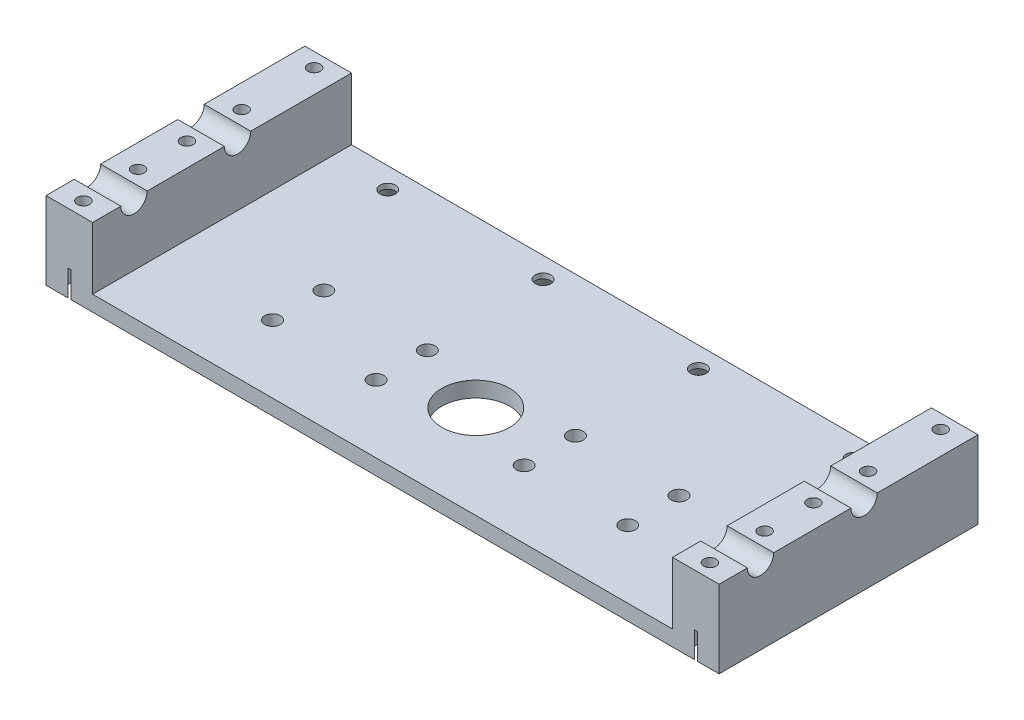
SolidWorks part; units mm, degrees
ref_plane "前视基准面" through (0, 0, 0) normal (0, 0, 1) x (1, 0, 0)
ref_plane "上视基准面" through (0, 0, 0) normal (0, 1, 0) x (1, 0, 0)
ref_plane "右视基准面" through (0, 0, 0) normal (1, 0, 0) x (0, 0, -1)
sketch "草图2" plane through (0, 0, 0) normal (1, 0, 0) x (0, 0, -1)
  line L0 (-7.45, 12) -> (7.45, 12)
  line L1 (-18, 0) -> (32, 0)
  line L2 (-18, 0) -> (-18, 12)
  line L3 (-18, 12) -> (-12.55, 12)
  line L4 (32, 0) -> (32, 12)
  line L5 (12.55, 12) -> (32, 12)
  arc A0 (7.45, 12) -> (12.55, 12) centre (10, 12) ccw
  arc A1 (-12.55, 12) -> (-7.45, 12) centre (-10, 12) ccw
  dimension "D4" = 5.1
  dimension "D5" = 5.1
  dimension "D1" = 12
  dimension "D2" = 50
  dimension "D3" = 18
  dimension "D6" = 20
  dimension "D7" = 10
extrude "凸台-拉伸1" add sketch "草图2" along normal mid plane 130
sketch "草图4" plane through (0, 0, 0) normal (0, -1, 0) x (1, 0, 0)
  line L0 (65, -32) -> (-65, -32) construction
  line L1 (-56, -32) -> (56, -32)
  line L2 (-56, -32) -> (-56, 18)
  line L3 (-56, 18) -> (56, 18)
  line L4 (56, -32) -> (56, 18)
  line L5 (65, 18) -> (-65, 18) construction
  dimension "D1" = 112
  dimension "D2" = 56
extrude "切除-拉伸1" cut sketch "草图4" against normal blind 20
sketch "草图5" plane through (0, 0, 0) normal (0, -1, 0) x (1, 0, 0)
  line L0 (-37.5732, 0) -> (40.267, 0) construction
  line L1 (-65, 18) -> (65, 18)
  line L2 (-65, 18) -> (-65, -32)
  line L3 (-65, -32) -> (65, -32)
  line L4 (65, 18) -> (65, -32)
  line L5 (0, 0) -> (0, -10.8475) construction
  circle A0 centre (0, 0) radius 6.55
  circle A1 centre (-14.3, 4.95) radius 1.5
  circle A2 centre (34.3, -4.95) radius 1.5
  circle A3 centre (34.3, 4.95) radius 1.5
  circle A4 centre (-14.3, -4.95) radius 1.5
  circle A5 centre (-34.3, 4.95) radius 1.5
  circle A6 centre (-34.3, -4.95) radius 1.5
  circle A7 centre (14.3, -4.95) radius 1.5
  circle A8 centre (14.3, 4.95) radius 1.5
  dimension "D2" = 13.1
  dimension "D3" = 3
  dimension "D7" = 3
  dimension "D1" = 50
  dimension "D4" = 4.95
  dimension "D5" = 34.3
  dimension "D6" = 48.6
extrude "凸台-拉伸2" add sketch "草图5" along normal blind 3
sketch "草图6" plane through (0, 12, 0) normal (0, 1, 0) x (1, 0, 0)
  line L0 (-60.5, 32) -> (-60.5, -18) construction
  line L1 (-56, 32) -> (-65, 32) construction
  line L2 (-56, -18) -> (-65, -18) construction
  line L3 (-65, -15.275) -> (-56, -15.275) construction
  line L4 (-65, -12.55) -> (-65, -18) construction
  line L5 (-56, -18) -> (-56, -12.55) construction
  line L6 (-65, -10) -> (-57.051, -10) construction
  line L7 (-65, -7.45) -> (-65, -12.55) construction
  line L8 (-65, 0) -> (-57.051, 0) construction
  line L9 (-65, 7.45) -> (-65, -7.45) construction
  line L10 (-65, 22.275) -> (-50.7357, 22.275) construction
  line L11 (-65, 32) -> (-65, 12.55) construction
  line L12 (0, 0) -> (0, 35.7346) construction
  circle A0 centre (-60.5, -15.275) radius 1.2
  circle A1 centre (-60.5, -4.725) radius 1.2
  circle A2 centre (-60.5, 15.275) radius 1.2
  circle A3 centre (-60.5, 4.725) radius 1.2
  circle A4 centre (-60.5, 29.275) radius 1.2
  circle A5 centre (60.5, 29.275) radius 1.2
  circle A6 centre (60.5, 4.725) radius 1.2
  circle A7 centre (60.5, 15.275) radius 1.2
  circle A8 centre (60.5, -4.725) radius 1.2
  circle A9 centre (60.5, -15.275) radius 1.2
  dimension "D1" = 2.4
extrude "切除-拉伸2" cut sketch "草图6" against normal blind 20
sketch "草图7" plane through (0, -3, 0) normal (0, -1, 0) x (1, 0, 0)
  line L0 (-65, -28) -> (69.8008, -28) construction
  line L1 (-65, 18) -> (-65, -32) construction
  line L2 (0, 0) -> (0, -29.8452) construction
  circle A0 centre (-15, -28) radius 1.5
  circle A1 centre (-45, -28) radius 1.5
  circle A2 centre (45, -28) radius 1.5
  circle A3 centre (15, -28) radius 1.5
  dimension "D2" = 3
  dimension "D4" = 3
  dimension "D1" = 4
  dimension "D3" = 15
  dimension "D5" = 30
extrude "切除-拉伸3" cut sketch "草图7" against normal blind 20
sketch "草图8" plane through (0, -3, 0) normal (0, -1, 0) x (1, 0, 0)
  line L0 (0, 0) -> (0, -34.2029) construction
  circle A0 centre (-45, -28) radius 2.65
  circle A1 centre (-15, -28) radius 2.65
  circle A2 centre (15, -28) radius 2.65
  circle A3 centre (45, -28) radius 2.65
  dimension "D1" = 5.3
  dimension "D2" = 5.3
extrude "切除-拉伸4" cut sketch "草图8" against normal blind 2 draft 25
sketch "草图9" plane through (0, -3, 0) normal (0, -1, 0) x (1, 0, 0)
  line L1 (-58, -3.2816) -> (-60.5, -1.8382)
  line L2 (-60.5, -1.8382) -> (-63, -3.2816)
  line L3 (-63, -3.2816) -> (-63, -6.1684)
  line L4 (-63, -6.1684) -> (-60.5, -7.6118)
  line L5 (-60.5, -7.6118) -> (-58, -6.1684)
  line L6 (-58, -6.1684) -> (-58, -3.2816)
  line L7 (-58, -13.8316) -> (-60.5, -12.3882)
  line L8 (-60.5, -12.3882) -> (-63, -13.8316)
  line L9 (-63, -13.8316) -> (-63, -16.7184)
  line L10 (-63, -16.7184) -> (-60.5, -18.1618)
  line L11 (-60.5, -18.1618) -> (-58, -16.7184)
  line L12 (-58, -16.7184) -> (-58, -13.8316)
  line L13 (-58, -27.8316) -> (-60.5, -26.3882)
  line L14 (-60.5, -26.3882) -> (-63, -27.8316)
  line L15 (-63, -27.8316) -> (-63, -30.7184)
  line L16 (-63, -30.7184) -> (-60.5, -32.1618)
  line L17 (-60.5, -32.1618) -> (-58, -30.7184)
  line L18 (-58, -30.7184) -> (-58, -27.8316)
  line L19 (-58, 6.1684) -> (-60.5, 7.6118)
  line L20 (-60.5, 7.6118) -> (-63, 6.1684)
  line L21 (-63, 6.1684) -> (-63, 3.2816)
  line L22 (-63, 3.2816) -> (-60.5, 1.8382)
  line L23 (-60.5, 1.8382) -> (-58, 3.2816)
  line L24 (-58, 3.2816) -> (-58, 6.1684)
  line L25 (-58, 13.8316) -> (-58, 16.7184)
  line L26 (-58, 16.7184) -> (-60.5, 18.1618)
  line L27 (-60.5, 18.1618) -> (-63, 16.7184)
  line L28 (-63, 16.7184) -> (-63, 13.8316)
  line L29 (-63, 13.8316) -> (-60.5, 12.3882)
  line L30 (-60.5, 12.3882) -> (-58, 13.8316)
  line L32 (0, 0) -> (0, 28.3404) construction
  line L33 (60.5, 12.3882) -> (58, 13.8316)
  line L34 (63, 13.8316) -> (60.5, 12.3882)
  line L35 (63, 16.7184) -> (63, 13.8316)
  line L36 (60.5, 18.1618) -> (63, 16.7184)
  line L37 (58, 16.7184) -> (60.5, 18.1618)
  line L38 (58, 13.8316) -> (58, 16.7184)
  line L39 (58, 3.2816) -> (58, 6.1684)
  line L40 (60.5, 1.8382) -> (58, 3.2816)
  line L41 (63, 3.2816) -> (60.5, 1.8382)
  line L42 (63, 6.1684) -> (63, 3.2816)
  line L43 (60.5, 7.6118) -> (63, 6.1684)
  line L44 (58, 6.1684) -> (60.5, 7.6118)
  line L45 (58, -30.7184) -> (58, -27.8316)
  line L46 (60.5, -32.1618) -> (58, -30.7184)
  line L47 (63, -30.7184) -> (60.5, -32.1618)
  line L48 (63, -27.8316) -> (63, -30.7184)
  line L49 (60.5, -26.3882) -> (63, -27.8316)
  line L50 (58, -27.8316) -> (60.5, -26.3882)
  line L51 (58, -16.7184) -> (58, -13.8316)
  line L52 (60.5, -18.1618) -> (58, -16.7184)
  line L53 (63, -16.7184) -> (60.5, -18.1618)
  line L54 (63, -13.8316) -> (63, -16.7184)
  line L55 (60.5, -12.3882) -> (63, -13.8316)
  line L56 (58, -13.8316) -> (60.5, -12.3882)
  line L57 (58, -6.1684) -> (58, -3.2816)
  line L58 (60.5, -7.6118) -> (58, -6.1684)
  line L59 (63, -6.1684) -> (60.5, -7.6118)
  line L60 (63, -3.2816) -> (63, -6.1684)
  line L61 (60.5, -1.8382) -> (63, -3.2816)
  line L62 (58, -3.2816) -> (60.5, -1.8382)
  circle A0 centre (-60.5, -4.725) radius 2.5 construction
  circle A1 centre (-60.5, -15.275) radius 2.5 construction
  circle A2 centre (-60.5, -29.275) radius 2.5 construction
  circle A3 centre (-60.5, 4.725) radius 2.5 construction
  circle A4 centre (-60.5, 15.275) radius 2.5 construction
  circle A5 centre (60.5, 15.275) radius 2.5 construction
  circle A6 centre (60.5, 4.725) radius 2.5 construction
  circle A7 centre (60.5, -29.275) radius 2.5 construction
  circle A8 centre (60.5, -15.275) radius 2.5 construction
  circle A9 centre (60.5, -4.725) radius 2.5 construction
  dimension "D1" = 5
  dimension "D2" = 5
  dimension "D3" = 5
  dimension "D4" = 5
  dimension "D5" = 5
extrude "切除-拉伸5" cut sketch "草图9" against normal blind 5
